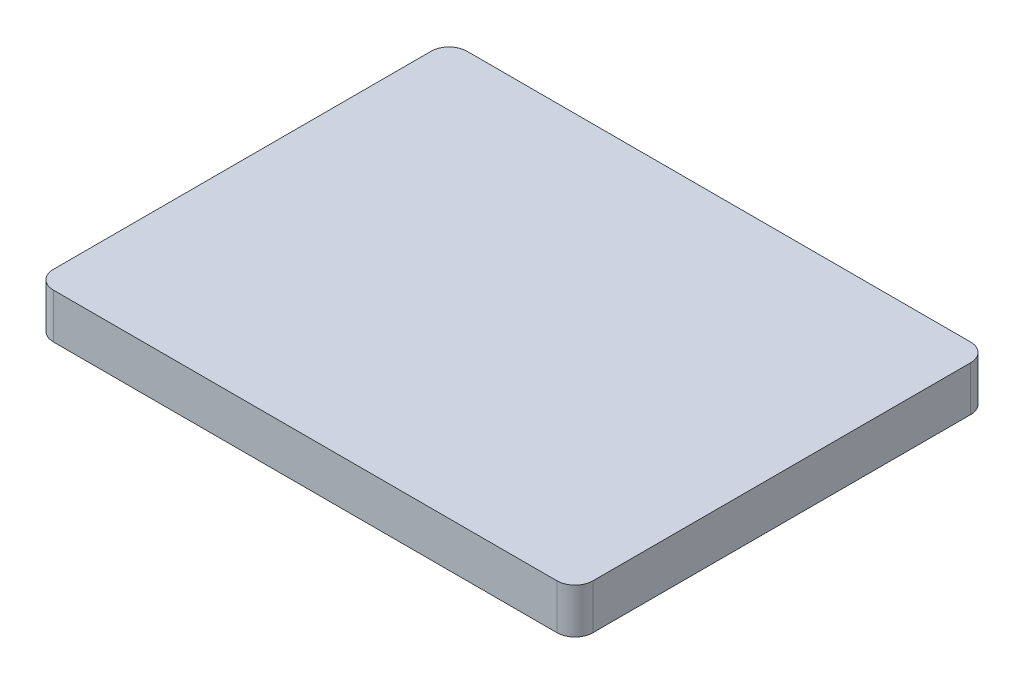
SolidWorks part; units mm, degrees
ref_plane "Front Plane" through (0, 0, 0) normal (0, 0, 1) x (1, 0, 0)
ref_plane "Top Plane" through (0, 0, 0) normal (0, 1, 0) x (1, 0, 0)
ref_plane "Right Plane" through (0, 0, 0) normal (1, 0, 0) x (0, 0, -1)
sketch "Sketch1" plane through (0, 0, 0) normal (0, 1, 0) x (1, 0, 0)
  line L5 (150, 115) -> (-150, 115)
  line L6 (150, 115) -> (150, -115)
  line L7 (150, -115) -> (-150, -115)
  line L8 (-150, 115) -> (-150, -115)
  line L9 (150, 115) -> (-150, -115) construction
  line L10 (150, -115) -> (-150, 115) construction
  point P0 (0, 0)
  dimension "D1" = 300
  dimension "D2" = 230
extrude "Boss-Extrude1" add sketch "Sketch1" along normal blind 25
fillet "Fillet1" radius 10 4 edges at (-150, 12.5, -115) (150, 12.5, -115) (150, 12.5, 115) (-150, 12.5, 115)
